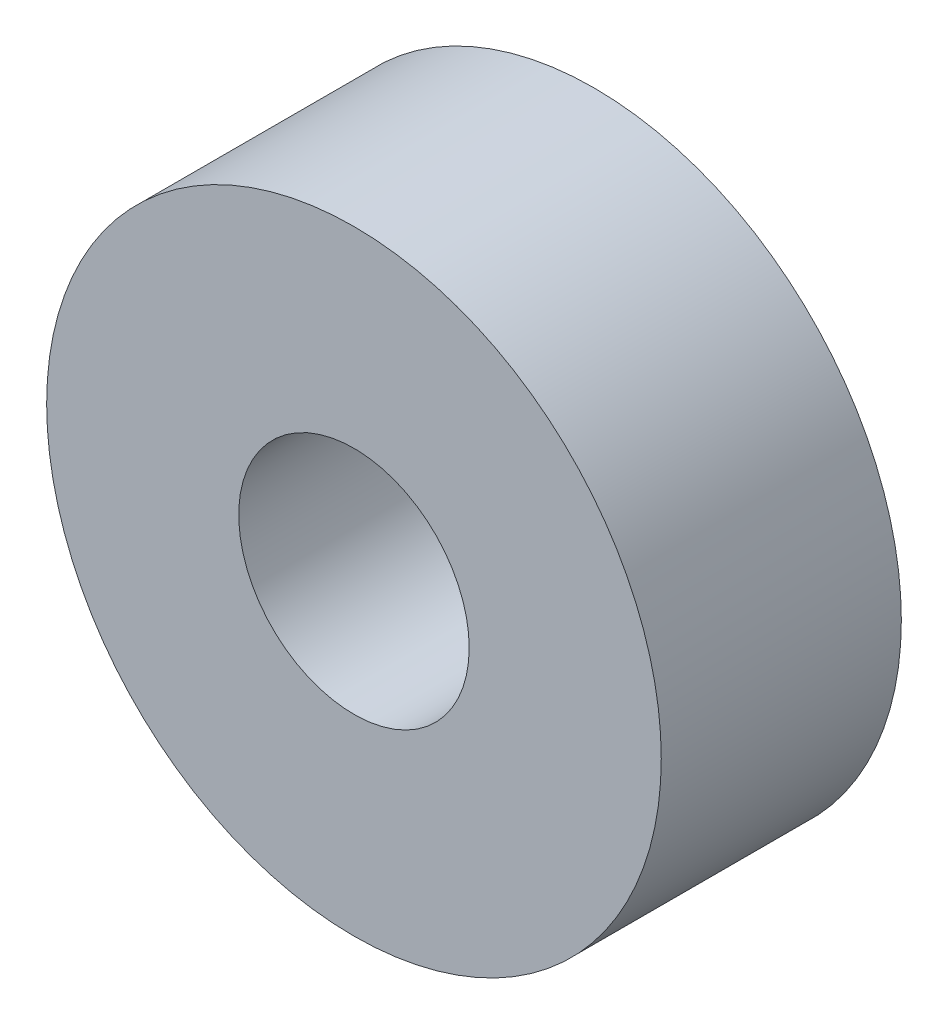
SolidWorks part; units mm, degrees
ref_plane "Front Plane" through (0, 0, 0) normal (0, 0, 1) x (1, 0, 0)
ref_plane "Top Plane" through (0, 0, 0) normal (0, 1, 0) x (1, 0, 0)
ref_plane "Right Plane" through (0, 0, 0) normal (1, 0, 0) x (0, 0, -1)
sketch "Sketch1" plane through (0, 0, 0) normal (0, 0, 1) x (1, 0, 0)
  circle A0 centre (0, 0) radius 2.4
  dimension "D1" = 4.8
extrude "Extrude-Thin1" add sketch "Sketch1" along normal blind 5 thin
